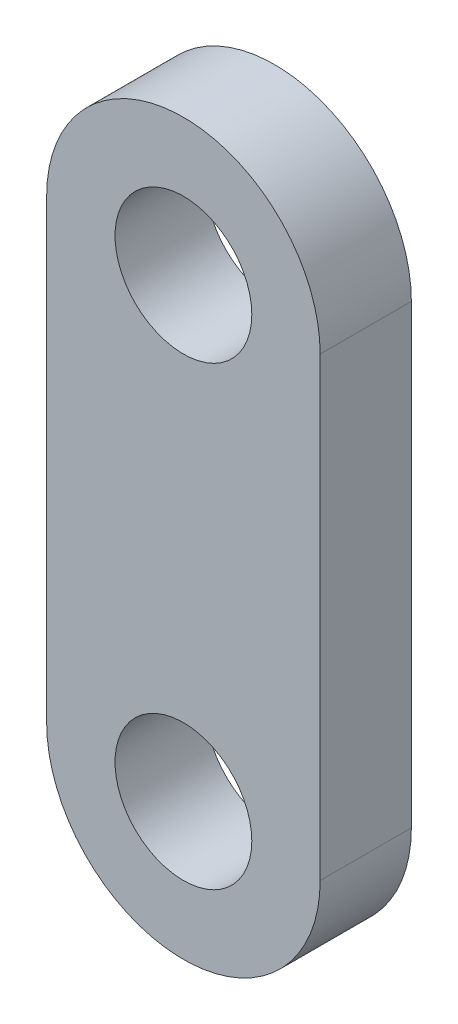
SolidWorks part; units mm, degrees
ref_plane "前视基准面" through (0, 0, 0) normal (0, 0, 1) x (1, 0, 0)
ref_plane "上视基准面" through (0, 0, 0) normal (0, 1, 0) x (1, 0, 0)
ref_plane "右视基准面" through (0, 0, 0) normal (1, 0, 0) x (0, 0, -1)
sketch "草图1" plane through (0, 0, 0) normal (0, 0, 1) x (1, 0, 0)
  line L0 (0, 0) -> (0, -10)
  line L1 (0, -5) -> (-1.072, -5) construction
  line L2 (3, 0) -> (3, -10)
  line L3 (-3, 0) -> (-3, -10)
  circle A0 centre (0, 0) radius 1.5
  circle A1 centre (0, -10) radius 1.5
  arc A2 (3, 0) -> (-3, 0) centre (0, 0) ccw
  arc A3 (3, -10) -> (-3, -10) centre (0, -10) cw
extrude "凸台-拉伸1" add sketch "草图1" along normal blind 2
